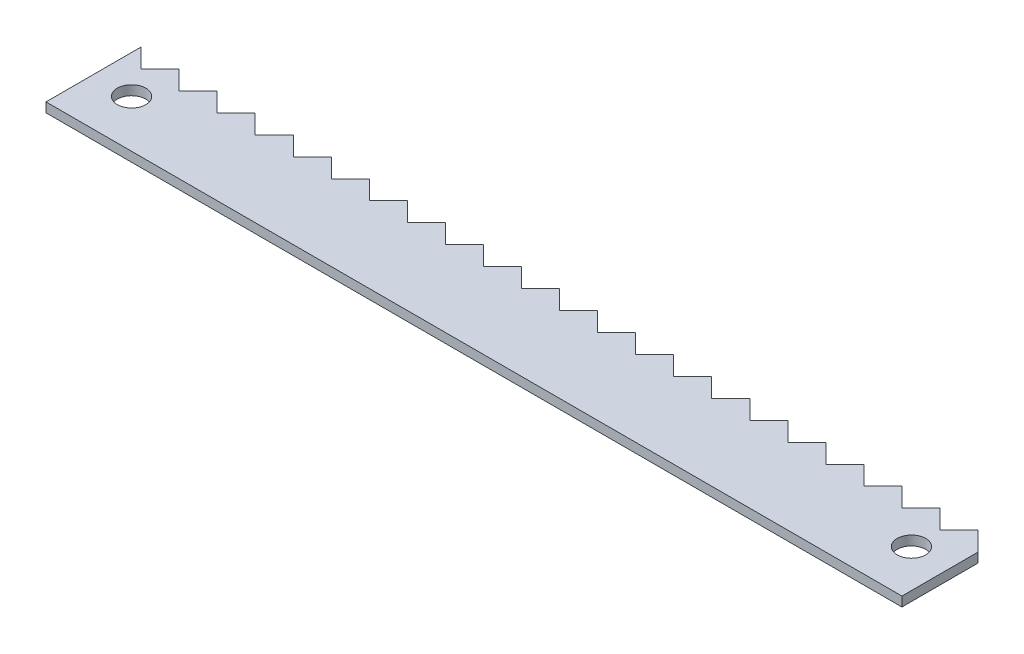
SolidWorks part; units mm, degrees
ref_plane "Front Plane" through (0, 0, 0) normal (0, 0, 1) x (1, 0, 0)
ref_plane "Top Plane" through (0, 0, 0) normal (0, 1, 0) x (1, 0, 0)
ref_plane "Right Plane" through (0, 0, 0) normal (1, 0, 0) x (0, 0, -1)
sketch "Sketch1" plane through (0, 0, 0) normal (0, 0, 1) x (1, 0, 0)
  line L1 (-90, 1) -> (90, 1)
  line L2 (-90, 1) -> (-90, -1)
  line L3 (-90, -1) -> (90, -1)
  line L4 (90, 1) -> (90, -1)
  line L5 (-90, 1) -> (90, -1) construction
  line L6 (-90, -1) -> (90, 1) construction
  point P0 (0, 0)
extrude "Boss-Extrude1" add sketch "Sketch1" along normal blind 20
sketch "Sketch2" plane through (0, 1, 0) normal (0, 1, 0) x (1, 0, 0)
  line L0 (90, 0) -> (-90, 0) construction
  line L1 (90, -20) -> (90, 0) construction
  line L2 (0, 5.552) -> (0, -26.6028) construction
  circle A0 centre (82, -10) radius 3
  circle A1 centre (-82, -10) radius 3
  dimension "D2" = 6
  dimension "D3" = 10
  dimension "D4" = 8
extrude "Cut-Extrude1" cut sketch "Sketch2" against normal blind 20
sketch "Sketch3" plane through (0, 1, 0) normal (0, 1, 0) x (1, 0, 0)
  line L1 (90, -4) -> (86, 0)
  line L2 (90, -4) -> (90, 0)
  line L4 (90, 0) -> (-90, 0) construction
  line L5 (86, 0) -> (82, -4)
  line L6 (82, -4) -> (78, 0)
  line L7 (78, 0) -> (74, -4)
  line L8 (74, -4) -> (70, 0)
  line L9 (70, 0) -> (66, -4)
  line L10 (66, -4) -> (62, 0)
  line L11 (62, 0) -> (58, -4)
  line L12 (58, -4) -> (54, 0)
  line L13 (54, 0) -> (50, -4)
  line L14 (50, -4) -> (46, 0)
  line L15 (46, 0) -> (42, -4)
  line L16 (42, -4) -> (38, 0)
  line L17 (38, 0) -> (34, -4)
  line L18 (34, -4) -> (30, 0)
  line L19 (30, 0) -> (26, -4)
  line L20 (26, -4) -> (22, 0)
  line L21 (22, 0) -> (18, -4)
  line L22 (18, -4) -> (14, 0)
  line L23 (14, 0) -> (10, -4)
  line L24 (10, -4) -> (6, 0)
  line L25 (6, 0) -> (2, -4)
  line L26 (2, -4) -> (-2, 0)
  line L27 (-2, 0) -> (-6, -4)
  line L28 (-6, -4) -> (-10, 0)
  line L29 (-10, 0) -> (-14, -4)
  line L30 (-14, -4) -> (-18, 0)
  line L31 (-18, 0) -> (-22, -4)
  line L32 (-22, -4) -> (-26, 0)
  line L33 (-26, 0) -> (-30, -4)
  line L34 (-30, -4) -> (-34, 0)
  line L35 (-34, 0) -> (-38, -4)
  line L36 (-38, -4) -> (-42, 0)
  line L37 (-42, 0) -> (-46, -4)
  line L38 (-46, -4) -> (-50, 0)
  line L39 (-50, 0) -> (-54, -4)
  line L40 (-54, -4) -> (-58, 0)
  line L41 (-58, 0) -> (-62, -4)
  line L42 (-62, -4) -> (-66, 0)
  line L43 (-66, 0) -> (-70, -4)
  line L44 (-70, -4) -> (-74, 0)
  line L45 (-74, 0) -> (-78, -4)
  line L46 (-78, -4) -> (-82, 0)
  line L47 (-82, 0) -> (-86, -4)
  line L48 (-86, -4) -> (-90, 0)
  line L50 (90, 0) -> (-90, 0)
  line L52 (-90, 0) -> (-94, -4) [skipped]
  line M50 (90, 0) -> (-90, 0)
  line M53 (90, -20) -> (90, 0)
  dimension "D2" = 23
extrude "Cut-Extrude2" cut sketch "Sketch3" against normal blind 20 contours L30 L29 M50 | L32 L31 M50 | L6 L5 M50 | L1 M53 M50 | L8 L7 M50 | L10 L9 M50 | L12 L11 M50 | L14 L13 M50 | L16 L15 M50 | L18 L17 M50 | L20 L19 M50 | L22 L21 M50 | L24 L23 M50 | L26 L25 M50 | L34 L33 M50 | L28 L27 M50 | L36 L35 M50 | L48 L47 M50 | L46 L45 M50 | L44 L43 M50 | L42 L41 M50 | L40 L39 M50 | L38 L37 M50
